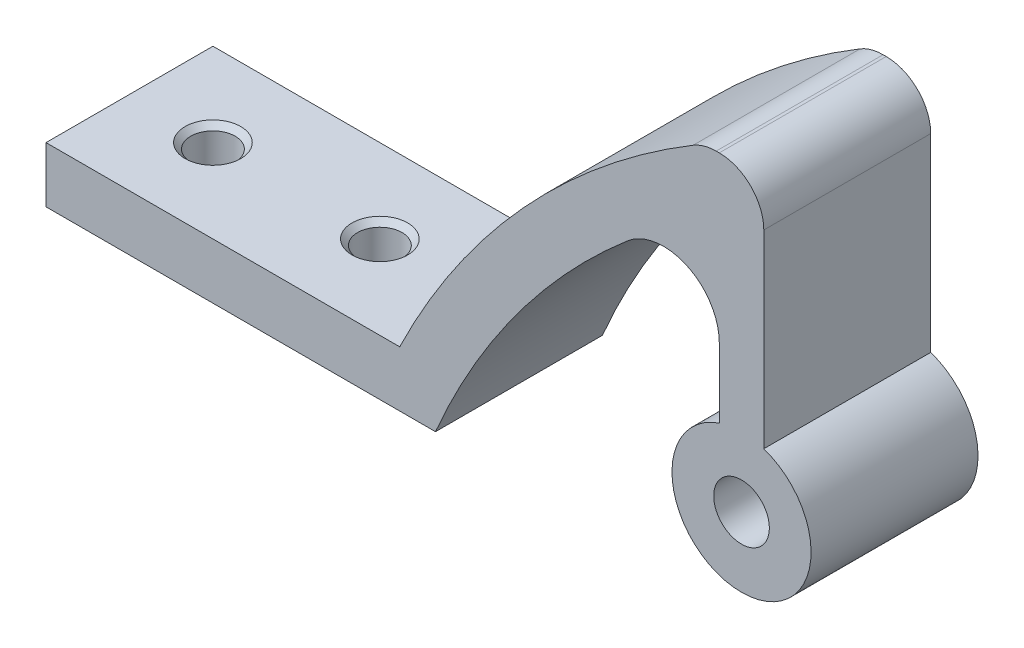
SolidWorks part; units mm, degrees
ref_plane "Front Plane" through (0, 0, 0) normal (0, 0, 1) x (1, 0, 0)
ref_plane "Top Plane" through (0, 0, 0) normal (0, 1, 0) x (1, 0, 0)
ref_plane "Right Plane" through (0, 0, 0) normal (1, 0, 0) x (0, 0, -1)
sketch "Sketch2" plane through (0, 0, 0) normal (0, 1, 0) x (1, 0, 0)
  line L0 (12.5, 7.5) -> (12.5, -7.5) construction
  line L1 (17.5, -7.5) -> (-17.5, -7.5)
  line L2 (17.5, -7.5) -> (17.5, 7.5)
  line L3 (17.5, 7.5) -> (-17.5, 7.5)
  line L4 (-17.5, -7.5) -> (-17.5, 7.5)
  line L5 (17.5, -7.5) -> (-17.5, 7.5) construction
  line L6 (17.5, 7.5) -> (-17.5, -7.5) construction
  circle A0 centre (-10, 0) radius 2
  circle A1 centre (5, 0) radius 2
  point P0 (0, 0)
  dimension "D5" = 4
  dimension "D6" = 4
  dimension "D1" = 15
  dimension "D2" = 35
  dimension "D3" = 15
  dimension "D4" = 10
  dimension "D7" = 5
extrude "Boss-Extrude1" add sketch "Sketch2" along normal blind 5
sketch "Sketch6" plane through (0, 0, 7.5) normal (0, 0, 1) x (1, 0, 0)
  line L0 (17.5, 0) -> (76.125, -25) construction
  line L1 (66.875, -5) -> (59, -5) construction
  line L2 (17.5, 0) -> (12.0998, 0) construction
  line L4 (17.5, 0) -> (12.0998, 0)
  line L5 (47, 14.25) -> (47, 20) construction
  line L6 (42.7209, 34.4484) -> (43, 34.4484)
  line L7 (43, 19.6771) -> (43, 7.5)
  line L8 (43, 7.5) -> (47, 7.5)
  line L9 (47, 30.4484) -> (47, 7.5)
  line L10 (76.125, -4) -> (76.125, -3) construction
  arc A0 (40.6568, 33.8747) -> (12.0998, 0) centre (76.125, -25) ccw
  arc A1 (34.7544, 23.4805) -> (17.5, 0) centre (76.125, -25) ccw
  arc A2 (43, 19.6771) -> (34.7544, 23.4805) centre (38, 19.6771) ccw
  circle A3 centre (45, 7.5) radius 2.5 construction
  arc A4 (43, 34.4484) -> (47, 30.4484) centre (43, 30.4484) cw
  arc A5 (42.7209, 34.4484) -> (40.6568, 33.8747) centre (42.7209, 30.4484) ccw
  point P3 (45, 7.5)
  point P11 (0, 0)
  point P14 (46.1663, 53.3157)
  point P29 (43, 29.4484)
  dimension "D1" = 5
  dimension "D2" = 4
  dimension "D5" = 5
  dimension "D7" = 4
  dimension "D3" = 20
  dimension "D4" = 5
extrude "Boss-Extrude6" add sketch "Sketch6" against normal blind 15
sketch "Sketch8" plane through (0, 0, 7.5) normal (0, 0, 1) x (1, 0, 0)
  line L0 (43, 7.5) -> (47, 7.5) construction
  circle A0 centre (45, 7.5) radius 6.25
  dimension "D1" = 12.5
extrude "Boss-Extrude7" add sketch "Sketch8" against normal blind 15
sketch "Sketch10" plane through (0, 0, 7.5) normal (0, 0, 1) x (1, 0, 0)
  circle A0 centre (45, 7.5) radius 2.5
  dimension "D1" = 5
extrude "Cut-Extrude1" cut sketch "Sketch10" against normal blind 15
chamfer "Chamfer1" distance 0.5 angle 45 2 edges at (5, 5, 2) (-10, 5, 2)
